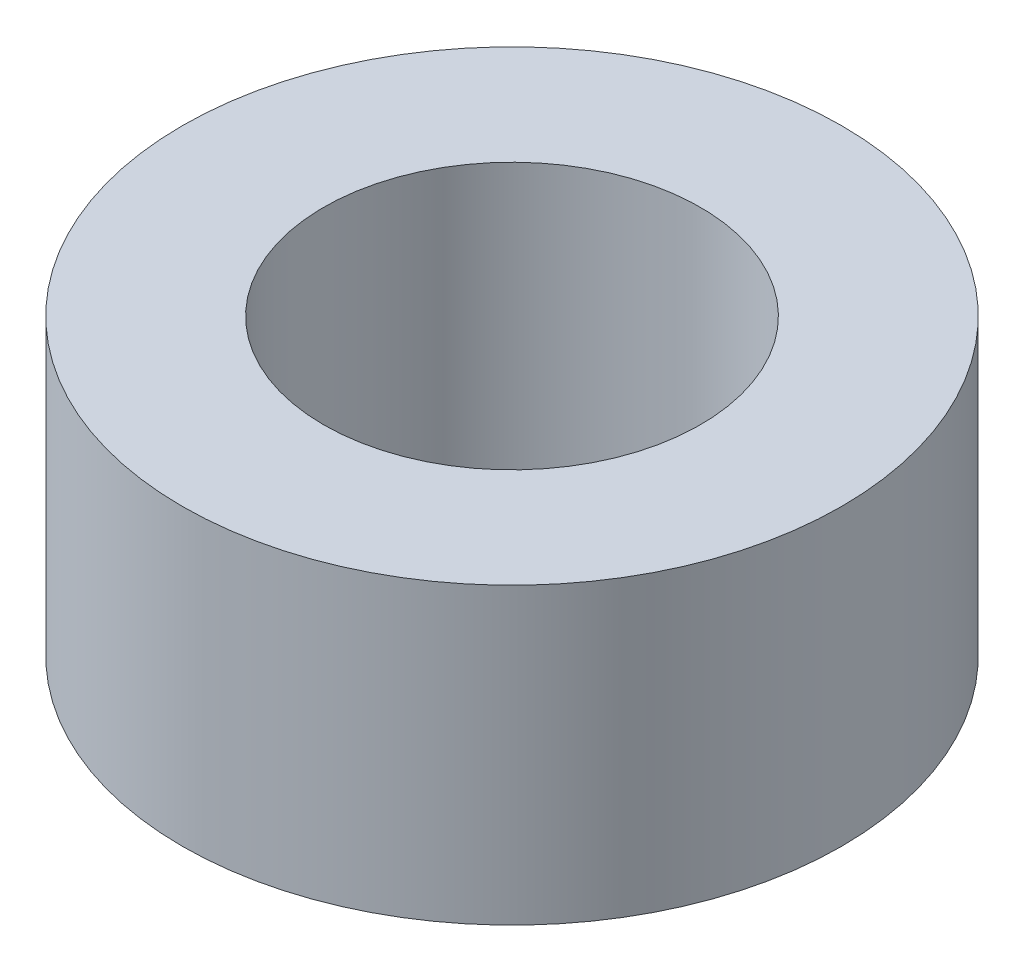
SolidWorks part; units mm, degrees
material "1060 Alloy"
ref_plane "Front Plane" through (0, 0, 0) normal (0, 0, 1) x (1, 0, 0)
ref_plane "Top Plane" through (0, 0, 0) normal (0, 1, 0) x (1, 0, 0)
ref_plane "Right Plane" through (0, 0, 0) normal (1, 0, 0) x (0, 0, -1)
sketch "Sketch1" plane through (0, 0, 0) normal (0, 1, 0) x (1, 0, 0)
  circle A0 centre (0, 0) radius 28
  circle A1 centre (0, 0) radius 16
extrude "Boss-Extrude1" add sketch "Sketch1" along normal blind 25
